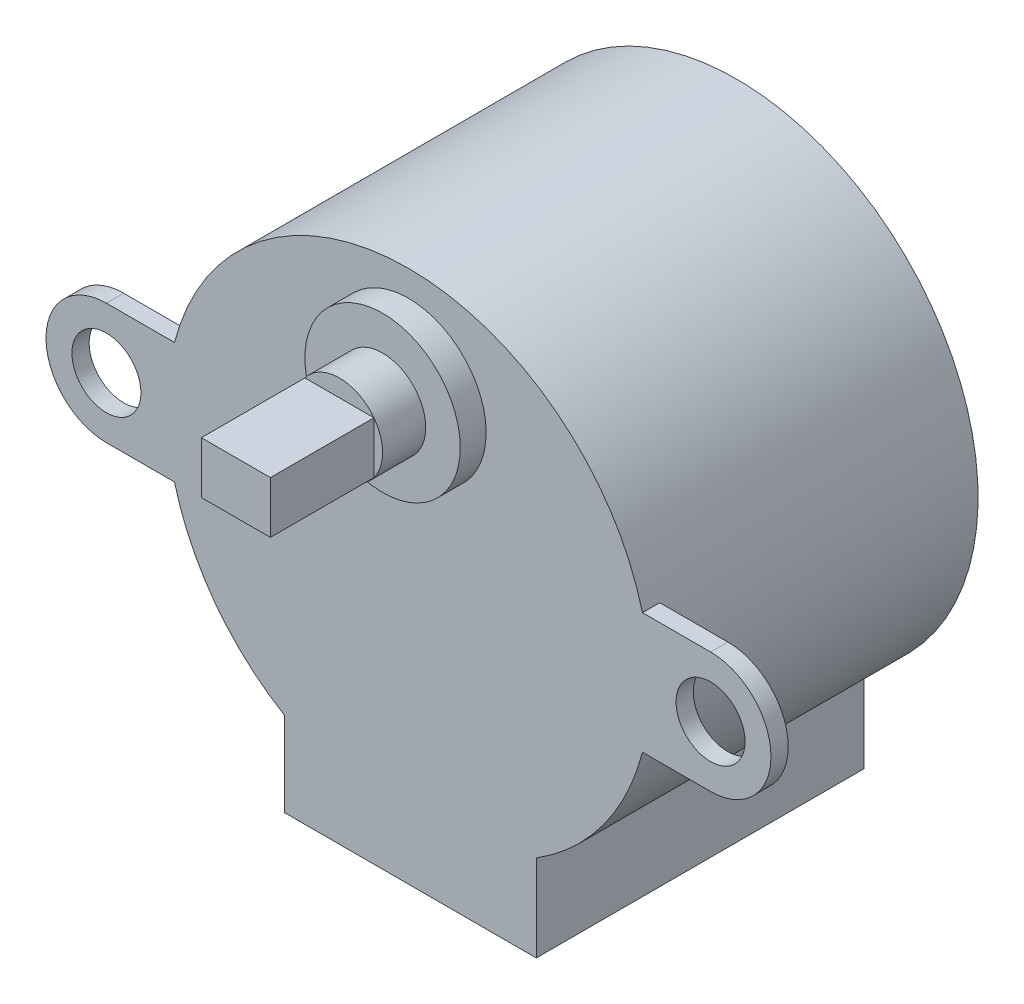
SolidWorks part; units mm, degrees
ref_plane "Plano frontal" through (0, 0, 0) normal (0, 0, 1) x (1, 0, 0)
ref_plane "Plano superior" through (0, 0, 0) normal (0, 1, 0) x (1, 0, 0)
ref_plane "Plano direito" through (0, 0, 0) normal (1, 0, 0) x (0, 0, -1)
sketch "Esboço2" plane through (0, 0, 0) normal (0, 0, 1) x (1, 0, 0)
  circle A0 centre (0, 0) radius 14
extrude "Ressalto-extrusão2" add sketch "Esboço2" along normal blind 19
sketch "Esboço3" plane through (0, 0, 19) normal (0, 0, 1) x (1, 0, 0)
  line L5 (-7.1957, -11.9016) -> (7.4043, -11.9016)
  line L6 (-7.1957, -11.9016) -> (-7.1957, -16.9016)
  line L7 (-7.1957, -16.9016) -> (7.4043, -16.9016)
  line L8 (7.4043, -11.9016) -> (7.4043, -16.9016)
  dimension "D1" = 14.6
  dimension "D2" = 5
extrude "Ressalto-extrusão3" add sketch "Esboço3" against normal blind 19 contours L6 L5 L8 L7
sketch "Esboço4" plane through (0, 0, 19) normal (0, 0, 1) x (1, 0, 0)
  line L0 (0, 0) -> (29.3246, 0)
  line L6 (13.3911, 3.5) -> (23.3911, 3.5)
  line L7 (13.3911, 3.5) -> (13.3911, -3.5)
  line L8 (13.3911, -3.5) -> (23.3911, -3.5)
  line L9 (23.3911, 3.5) -> (23.3911, -3.5)
  dimension "D1" = 7
  dimension "D2" = 10
  dimension "D3" = 3.5
extrude "Ressalto-extrusão4" add sketch "Esboço4" against normal blind 19
sketch "Esboço5" plane through (0, 0, 19) normal (0, 0, 1) x (1, 0, 0)
  line L0 (0, 0) -> (-22.6137, 0)
  line L1 (0, 0) -> (0, 14.98)
  line L3 (-23.354, 3.5) -> (-13.354, 3.5)
  line L4 (-23.354, 3.5) -> (-23.354, -3.5)
  line L5 (-23.354, -3.5) -> (-13.354, -3.5)
  line L6 (-13.354, 3.5) -> (-13.354, -3.5)
  dimension "D1" = 7
  dimension "D2" = 10
  dimension "D3" = 3.5
extrude "Ressalto-extrusão5" add sketch "Esboço5" against normal blind 19
sketch "Esboço6" plane through (0, 0, 19) normal (0, 0, 1) x (1, 0, 0)
  circle A0 centre (-17.5, 0) radius 2
  circle A1 centre (17.5, 0) radius 2
  dimension "D1" = 4
  dimension "D2" = 4
  dimension "D3" = 35
  dimension "D4" = 17.5
extrude "Corte-extrusão1" cut sketch "Esboço6" against normal through all
sketch "Esboço7" plane through (0, 0, 0) normal (0, 0, 1) x (1, 0, 0)
  point P0 (-17.5, 0)
  point P1 (0, 0)
  point P16 (-14.1529, 1.0233)
  line B0 (-17.5, 3.5) -> (-23.354, 3.5)
  line B1 (-23.354, 3.5) -> (-23.354, -3.5)
  line B2 (-23.354, -3.5) -> (-17.5, -3.5)
  arc B3 (-17.5, 3.5) -> (-17.5, -3.5) centre (-17.5, 0) ccw
sketch_block_instance "Bloco1-1"
sketch_block "Bloco1"
extrude "Corte-extrusão2" cut sketch "Esboço7" along normal through all
sketch "Esboço8" plane through (0, 0, 0) normal (0, 0, 1) x (1, 0, 0)
  line L0 (17.5, 3.5) -> (23.3911, 3.5)
  line L1 (23.3911, 3.5) -> (23.3911, -3.5)
  line L2 (23.3911, -3.5) -> (17.5, -3.5)
  arc A0 (17.5, -3.5) -> (17.5, 3.5) centre (17.5, 0) ccw
extrude "Corte-extrusão3" cut sketch "Esboço8" along normal through all
sketch "Esboço9" plane through (0, 0, 0) normal (0, 0, 1) x (1, 0, 0)
  circle A0 centre (0, 8) radius 4.5
  dimension "D1" = 9
  dimension "D2" = 8
extrude "Ressalto-extrusão7" add sketch "Esboço9" along normal blind 20.5
sketch "Esboço10" plane through (0, 0, 20.5) normal (0, 0, 1) x (1, 0, 0)
  circle A1 centre (0, 8) radius 2.5
  dimension "D1" = 5
extrude "Ressalto-extrusão8" add sketch "Esboço10" along normal blind 2.5
sketch "Esboço11" plane through (0, 0, 0) normal (0, 0, 1) x (1, 0, 0)
  line L1 (-2, 9.5) -> (2, 9.5)
  line L2 (-2, 9.5) -> (-2, 6.5)
  line L3 (-2, 6.5) -> (2, 6.5)
  line L4 (2, 9.5) -> (2, 6.5)
  circle A0 centre (0, 8) radius 2.5 construction
  circle A1 centre (0, 8) radius 2.5 construction
  dimension "D1" = 3
  dimension "D2" = 1.5
  dimension "D3" = 2
  dimension "D4" = 2
extrude "Ressalto-extrusão9" add sketch "Esboço11" along normal blind 29
sketch "Esboço12" plane through (0, 0, 0) normal (0, 0, -1) x (-1, 0, 0)
  line L0 (-17.5, -3.5) -> (-13.5554, -3.5)
  line L1 (-17.5, 3.5) -> (-13.5554, 3.5)
  arc A0 (-13.5554, 3.5) -> (-13.5554, -3.5) centre (0, 0) ccw
  arc A1 (-17.5, 3.5) -> (-17.5, -3.5) centre (-17.5, 0) ccw
extrude "Corte-extrusão4" cut sketch "Esboço12" against normal blind 18
sketch "Esboço13" plane through (0, 0, 0) normal (0, 0, -1) x (-1, 0, 0)
  line L0 (13.5554, -3.5) -> (17.5, -3.5)
  line L1 (17.5, 3.5) -> (13.5554, 3.5)
  arc A0 (13.5554, -3.5) -> (13.5554, 3.5) centre (0, 0) ccw
  arc A1 (17.5, -3.5) -> (17.5, 3.5) centre (17.5, 0) ccw
extrude "Corte-extrusão5" cut sketch "Esboço13" against normal blind 18
